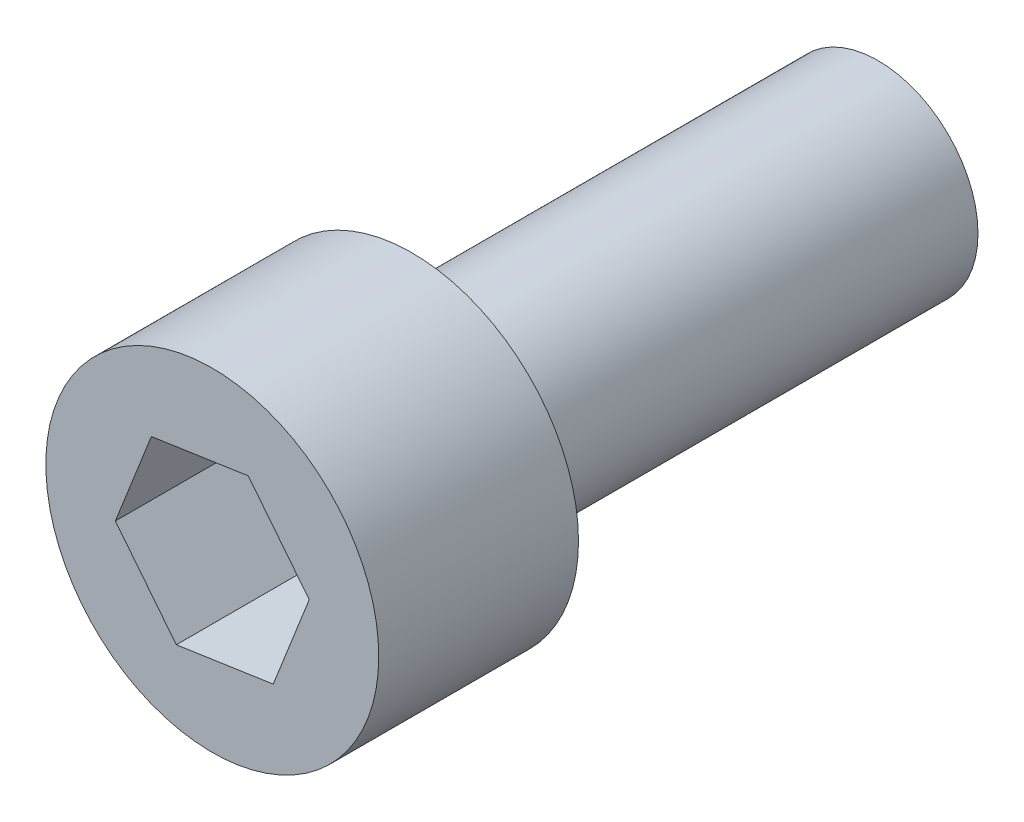
SolidWorks part; units mm, degrees
ref_plane "前视基准面" through (0, 0, 0) normal (0, 0, 1) x (1, 0, 0)
ref_plane "上视基准面" through (0, 0, 0) normal (0, 1, 0) x (1, 0, 0)
ref_plane "右视基准面" through (0, 0, 0) normal (1, 0, 0) x (0, 0, -1)
sketch "草图1" plane through (0, 0, 0) normal (0, 0, 1) x (1, 0, 0)
  circle A0 centre (0, 0) radius 3
  dimension "D1" = 6
extrude "拉伸1" add sketch "草图1" along normal blind 15
sketch "草图2" plane through (0, 0, 15) normal (0, 0, 1) x (1, 0, 0)
  line L1 (-1.8302, 2.3051) -> (-2.9113, -0.4325)
  line L2 (-2.9113, -0.4325) -> (-1.0812, -2.7375)
  line L3 (-1.0812, -2.7375) -> (1.8302, -2.3051)
  line L4 (1.8302, -2.3051) -> (2.9113, 0.4325)
  line L5 (2.9113, 0.4325) -> (1.0812, 2.7375)
  line L6 (1.0812, 2.7375) -> (-1.8302, 2.3051)
  circle A0 centre (0, 0) radius 5
  circle A1 centre (0, 0) radius 2.549 construction
  dimension "D1" = 10
extrude "拉伸2" add sketch "草图2" along normal blind 5 and the other way blind 1
